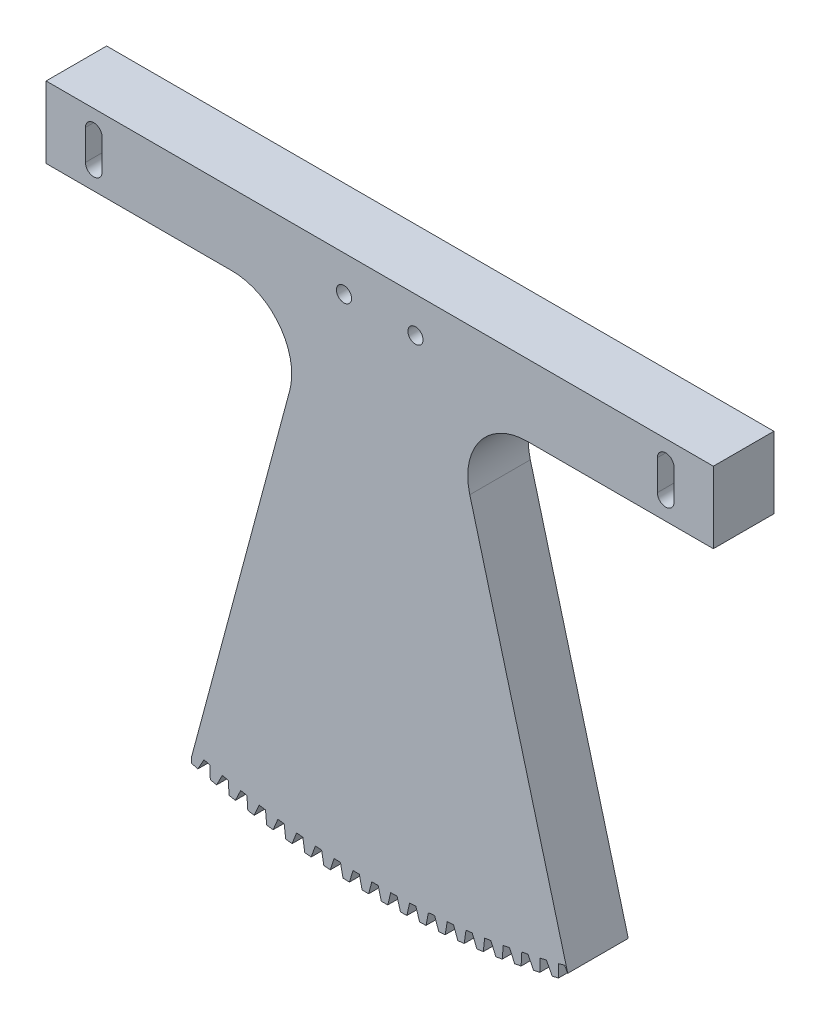
SolidWorks part; units mm, degrees
ref_plane "Front Plane" through (0, 0, 0) normal (0, 0, 1) x (1, 0, 0)
ref_plane "Top Plane" through (0, 0, 0) normal (0, 1, 0) x (1, 0, 0)
ref_plane "Right Plane" through (0, 0, 0) normal (1, 0, 0) x (0, 0, -1)
sketch "Sketch3" plane through (0, 0, 0) normal (0, 0, 1) x (1, 0, 0)
  line L0 (0, 0) -> (0, -304.8) construction
  line L1 (-21.234, -79.2464) -> (-78.888, -294.4142)
  line L2 (21.234, -79.2464) -> (78.888, -294.4142)
  line L4 (-140, -79.56) -> (140, -79.56)
  line L5 (-140, -79.56) -> (-140, -109.56)
  line L6 (-140, -109.56) -> (140, -109.56)
  line L7 (140, -79.56) -> (140, -109.56)
  line L8 (0, -109.56) -> (0, -79.56) construction
  line L9 (-140, -94.56) -> (140, -94.56) construction
  arc A0 (-78.888, -294.4142) -> (78.888, -294.4142) centre (0, 0) ccw
  point P269 (0, -94.56)
  dimension "D1" = 304.8
  dimension "D4" = 79.56
  dimension "D5" = 30
  dimension "D6" = 280
  dimension "D7" = 140
extrude "Boss-Extrude2" add sketch "Sketch3" along normal blind 25.4 contours L7 L4 L2 L6 | L1 L6 L2 L4 | L1 L4 L2 | L5 L6 L1 L4 | L1 A0 L2 L6
fillet "Fillet1" radius 25 2 edges at (-29.3565, -109.56, 12.7) (29.3565, -109.56, 12.7)
sketch "Sketch4" plane through (0, -79.56, 0) normal (0, 1, 0) x (1, 0, 0)
  line L1 (-140, 0) -> (140, 0)
  line L2 (-140, 0) -> (-140, -25.4)
  line L3 (-140, -25.4) -> (140, -25.4)
  line L4 (140, 0) -> (140, -25.4)
  line L5 (0, -25.4) -> (0, 0) construction
  line L6 (-140, -12.7) -> (140, -12.7) construction
  point P252 (0, -12.7)
sketch "Sketch5" plane through (0, 0, 0) normal (0, 0, -1) x (-1, 0, 0)
  line L0 (-123.5, -94.56) -> (-123.5, -100.91)
  line L1 (-116.5, -94.56) -> (-116.5, -100.91)
  line L2 (116.5, -94.56) -> (116.5, -88.21)
  line L3 (140, -79.56) -> (-140, -79.56) construction
  line L4 (-120, -88.21) -> (-120, -100.91) construction
  line L5 (0, -79.56) -> (0, -109.56) construction
  line L6 (-116.5, -94.56) -> (-116.5, -88.21)
  line L7 (-123.5, -94.56) -> (-123.5, -88.21)
  line L8 (116.5, -94.56) -> (116.5, -100.91)
  line L9 (123.5, -94.56) -> (123.5, -100.91)
  line L10 (123.5, -94.56) -> (123.5, -88.21)
  line L11 (-140, -79.56) -> (-140, -109.56) construction
  line L12 (120, -88.21) -> (120, -100.91) construction
  arc A1 (-116.5, -88.21) -> (-123.5, -88.21) centre (-120, -88.21) ccw
  arc A2 (-123.5, -100.91) -> (-116.5, -100.91) centre (-120, -100.91) ccw
  arc A3 (123.5, -100.91) -> (116.5, -100.91) centre (120, -100.91) cw
  arc A4 (116.5, -88.21) -> (123.5, -88.21) centre (120, -88.21) cw
  circle A5 centre (-15, -94.56) radius 3.175
  circle A6 centre (15, -94.56) radius 3.175
  dimension "D1" = 16.5
  dimension "D2" = 7
  dimension "D3" = 8.65
  dimension "D5" = 3.5
  dimension "D6" = 15
  dimension "D8" = 6.35
  dimension "D4" = 6.35
  dimension "D7" = 15
sketch "Sketch13" plane through (0, 0, 0) normal (0, 0, -1) x (-1, 0, 0)
  line L0 (0, 0) -> (78.888, -294.4142)
  line L1 (0, 0) -> (-78.888, -294.4142)
  arc A0 (-78.888, -294.4142) -> (78.888, -294.4142) centre (0, 0) ccw
  arc A1 (-78.888, -294.4142) -> (78.888, -294.4142) centre (0, 0) ccw construction
  arc A2 (-78.888, -294.4142) -> (78.888, -294.4142) centre (0, 0) ccw
  circle A3 centre (0, 0) radius 304.8
  dimension "D1" = 609.6
sketch "Sketch14" plane through (0, 0, 0) normal (0, 0, -1) x (-1, 0, 0)
  line L0 (0, 0) -> (80.0203, -298.6399) construction
  line L2 (78.888, -294.4142) -> (78.9109, -297.0369)
  line L3 (78.9109, -297.0369) -> (76.2891, -297.7211)
  line L18 (76.2891, -297.7211) -> (75.0275, -295.4216)
  line L20 (0, 0) -> (-79.2746, -295.8555) construction
  line L32 (78.888, -294.4142) -> (75.0275, -295.4216)
  line L33 (75.0275, -295.4216) -> (78.888, -294.4142)
  line L34 (0, 0) -> (-75.3952, -296.8678) construction
  line L35 (0, 0) -> (-71.5028, -297.8293) construction
  line L36 (0, 0) -> (-67.5982, -298.7397) construction
  line L37 (0, 0) -> (-63.6821, -299.5989) construction
  line L38 (0, 0) -> (-59.755, -300.4068) construction
  line L39 (0, 0) -> (-55.8176, -301.1633) construction
  line L40 (0, 0) -> (-51.8707, -301.8681) construction
  line L41 (0, 0) -> (-47.9149, -302.5212) construction
  line L42 (0, 0) -> (-43.951, -303.1225) construction
  line L43 (0, 0) -> (-39.9794, -303.6718) construction
  line L44 (0, 0) -> (-36.0011, -304.1691) construction
  line L45 (0, 0) -> (-32.0165, -304.6143) construction
  line L46 (0, 0) -> (-28.0265, -305.0073) construction
  line L47 (0, 0) -> (-24.0316, -305.348) construction
  line L48 (0, 0) -> (-20.0327, -305.6364) construction
  line L49 (0, 0) -> (-16.0303, -305.8724) construction
  line L50 (0, 0) -> (-12.0252, -306.0561) construction
  line L51 (0, 0) -> (-8.018, -306.1873) construction
  line L52 (0, 0) -> (-4.0094, -306.266) construction
  line L53 (0, 0) -> (-0.0002, -306.2922) construction
  line L54 (0, 0) -> (4.0091, -306.266) construction
  line L55 (0, 0) -> (8.0176, -306.1873) construction
  line L56 (0, 0) -> (12.0248, -306.0561) construction
  line L57 (0, 0) -> (16.03, -305.8725) construction
  line L58 (0, 0) -> (20.0323, -305.6364) construction
  line L59 (0, 0) -> (24.0313, -305.348) construction
  line L60 (0, 0) -> (28.0261, -305.0073) construction
  line L61 (0, 0) -> (32.0162, -304.6143) construction
  line L62 (0, 0) -> (36.0007, -304.1691) construction
  line L63 (0, 0) -> (39.9791, -303.6719) construction
  line L64 (0, 0) -> (43.9506, -303.1225) construction
  line L65 (0, 0) -> (47.9146, -302.5213) construction
  line L66 (0, 0) -> (51.8704, -301.8682) construction
  line L67 (0, 0) -> (55.8173, -301.1633) construction
  line L68 (0, 0) -> (59.7546, -300.4069) construction
  line L69 (0, 0) -> (63.6817, -299.599) construction
  line L70 (0, 0) -> (67.5979, -298.7398) construction
  line L71 (0, 0) -> (71.5025, -297.8293) construction
  line L72 (0, 0) -> (75.3948, -296.8679) construction
  line L73 (0, 0) -> (-79.2746, -295.8555) construction
  line L74 (0, 0) -> (-75.3952, -296.8678) construction
  line L137 (37.789, -141.0305) -> (78.888, -294.4142) construction
  line L138 (-140, -79.56) -> (-140, -109.56)
  line L139 (-140, -109.56) -> (-61.9371, -109.56)
  line L140 (-37.789, -141.0305) -> (-78.888, -294.4142)
  line L141 (78.888, -294.4142) -> (37.789, -141.0305)
  line L142 (61.9371, -109.56) -> (140, -109.56)
  line L143 (140, -109.56) -> (140, -79.56)
  line L144 (140, -79.56) -> (-140, -79.56)
  line L145 (-140, -79.56) -> (-140, -109.56)
  line L146 (-140, -109.56) -> (-61.9371, -109.56)
  line L147 (-37.789, -141.0305) -> (-78.888, -294.4142)
  line L149 (61.9371, -109.56) -> (140, -109.56)
  line L150 (140, -109.56) -> (140, -79.56)
  line L151 (140, -79.56) -> (-140, -79.56)
  circle A0 centre (0, 0) radius 307.34
  circle A1 centre (0, 0) radius 302.26
  arc A3 (-37.789, -141.0305) -> (-61.9371, -109.56) centre (-61.9371, -134.56) ccw
  arc A5 (61.9371, -109.56) -> (37.789, -141.0305) centre (61.9371, -134.56) ccw
  arc A6 (-37.789, -141.0305) -> (-61.9371, -109.56) centre (-61.9371, -134.56) ccw
  arc A8 (61.9371, -109.56) -> (37.789, -141.0305) centre (61.9371, -134.56) ccw
  arc A11 (-78.888, -294.4142) -> (78.888, -294.4142) centre (0, 0) ccw
  arc A12 (-78.888, -294.4142) -> (78.888, -294.4142) centre (0, 0) ccw
  dimension "D5" = 614.68
  dimension "D6" = 30
  dimension "D7" = 40
  dimension "D4" = 604.52
  dimension "D1" = 14.5
  dimension "D3" = 14.5
  dimension "D8" = 0.75
  dimension "D9" = 306.2922
  dimension "D10" = 0.75
  dimension "D2" = 0
extrude "Boss-Extrude4" add sketch "Sketch14" against normal up to surface (25.4 mm away) up to face at (0, -146.6727, 25.4)
sketch "Sketch15" plane through (0, 0, 0) normal (1, 0, 0) x (0, 0, -1)
  line L0 (0, 0) -> (-23.3364, 0) construction
sketch "Sketch16" plane through (0, 0, 0) normal (0, 0, -1) x (-1, 0, 0)
  line L0 (75.0275, -295.4216) -> (73.7653, -293.1208)
  line L1 (73.7653, -293.1208) -> (71.1999, -293.7544)
  line L2 (71.1999, -293.7544) -> (71.1541, -296.3784)
  line L3 (0, 0) -> (71.5025, -297.8293) construction
  line L4 (0, 0) -> (75.3948, -296.8679) construction
  circle A0 centre (0, 0) radius 302.26 construction
  arc A1 (-78.888, -294.4142) -> (78.888, -294.4142) centre (0, 0) ccw construction
  dimension "D1" = 14.5
  dimension "D2" = 14.5
extrude "Cut-Extrude2" cut sketch "Sketch16" against normal through all and the other way through all
pattern_circular "CirPattern8" count 20 every 1.5 about axis through (0, 0, 0) along (0, 0, 1) of "Cut-Extrude2", "Boss-Extrude4"
extrude "Cut-Extrude3" cut sketch "Sketch5" against normal through all
equation "\"D7@Sketch3\"=\"D6@Sketch3\"/2"
